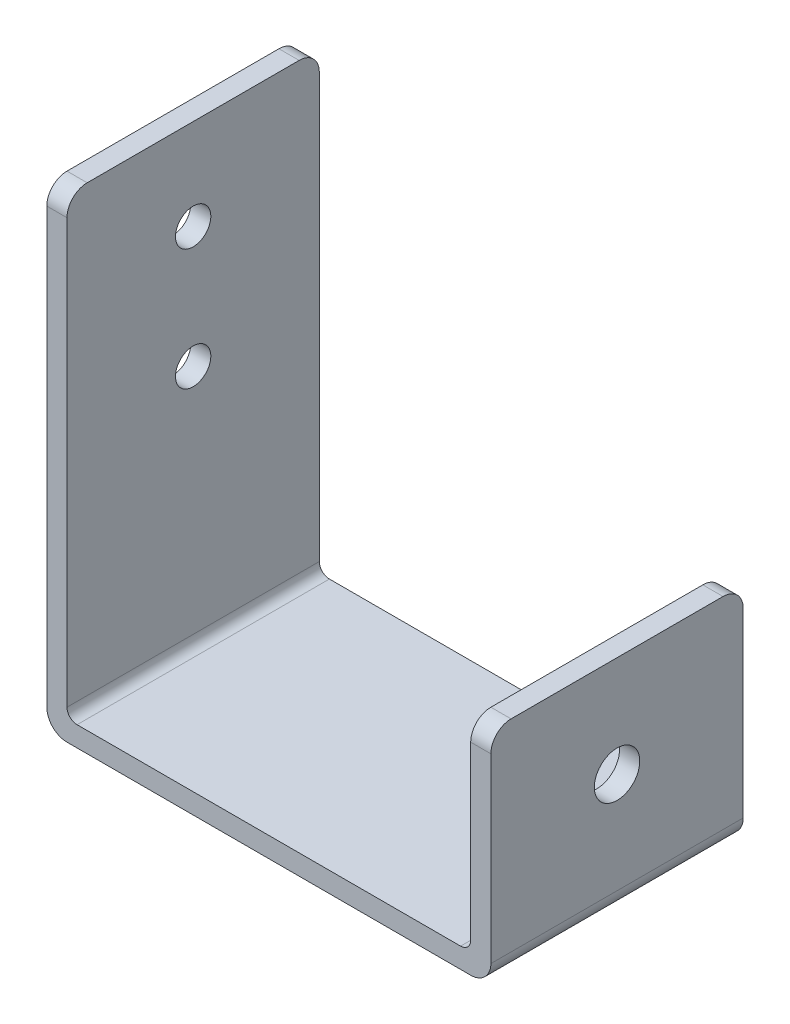
SolidWorks part; units mm, degrees
ref_plane "Plan de face" through (0, 0, 0) normal (0, 0, 1) x (1, 0, 0)
ref_plane "Plan de dessus" through (0, 0, 0) normal (0, 1, 0) x (1, 0, 0)
ref_plane "Plan de droite" through (0, 0, 0) normal (1, 0, 0) x (0, 0, -1)
sketch "Esquisse1" plane through (0, 0, 0) normal (0, 0, 1) x (1, 0, 0)
  line L0 (0, 0) -> (40, 0)
  line L1 (0, 0) -> (0, 45)
  line L2 (40, 0) -> (40, 20)
  dimension "D1" = 40
  dimension "D2" = 20
  dimension "D3" = 45
extrude "Extru.-Mince1" add sketch "Esquisse1" along normal blind 25 thin
fillet "Congé1" radius 1 1 edges at (0, 0, 12.5)
fillet "Congé2" radius 1 1 edges at (40, 0, 12.5)
fillet "Congé3" radius 2 1 edges at (42, -2, 12.5)
fillet "Congé4" radius 2 1 edges at (-2, -2, 12.5)
sketch "Esquisse2" plane through (-2, 0, 0) normal (-1, 0, 0) x (0, 0, 1)
  line L0 (-4.3852, 30) -> (27.735, 30) construction
  line L1 (12.5, 41.2385) -> (12.5, 10.4299) construction
  line L2 (0, 45) -> (0, 0) construction
  line L3 (25, 45) -> (0, 45) construction
  circle A0 centre (12.5, 36) radius 1.75
  circle A1 centre (12.5, 24) radius 1.75
  dimension "D7" = 3.5
  dimension "D10" = 3.5
  dimension "D1" = 12.5
  dimension "D2" = 15
  dimension "D3" = 6
  dimension "D4" = 6
extrude "Enlèv. mat.-Extru.1" cut sketch "Esquisse2" against normal blind 2
sketch "Esquisse3" plane through (42, 0, 0) normal (1, 0, 0) x (0, 0, -1)
  line L0 (0, -2) -> (-25, -2) construction
  line L1 (-25, 0) -> (-25, 20) construction
  circle A0 centre (-12.5, 10) radius 2.25
  dimension "D1" = 4.5
  dimension "D2" = 12
  dimension "D3" = 12.5
extrude "Enlèv. mat.-Extru.2" cut sketch "Esquisse3" against normal blind 2
fillet "Congé12" radius 2 1 edges at (41, 20, 0)
fillet "Congé13" radius 2 1 edges at (41, 20, 25)
fillet "Congé15" radius 2 1 edges at (-1, 45, 0)
fillet "Congé16" radius 2 1 edges at (-1, 45, 25)
